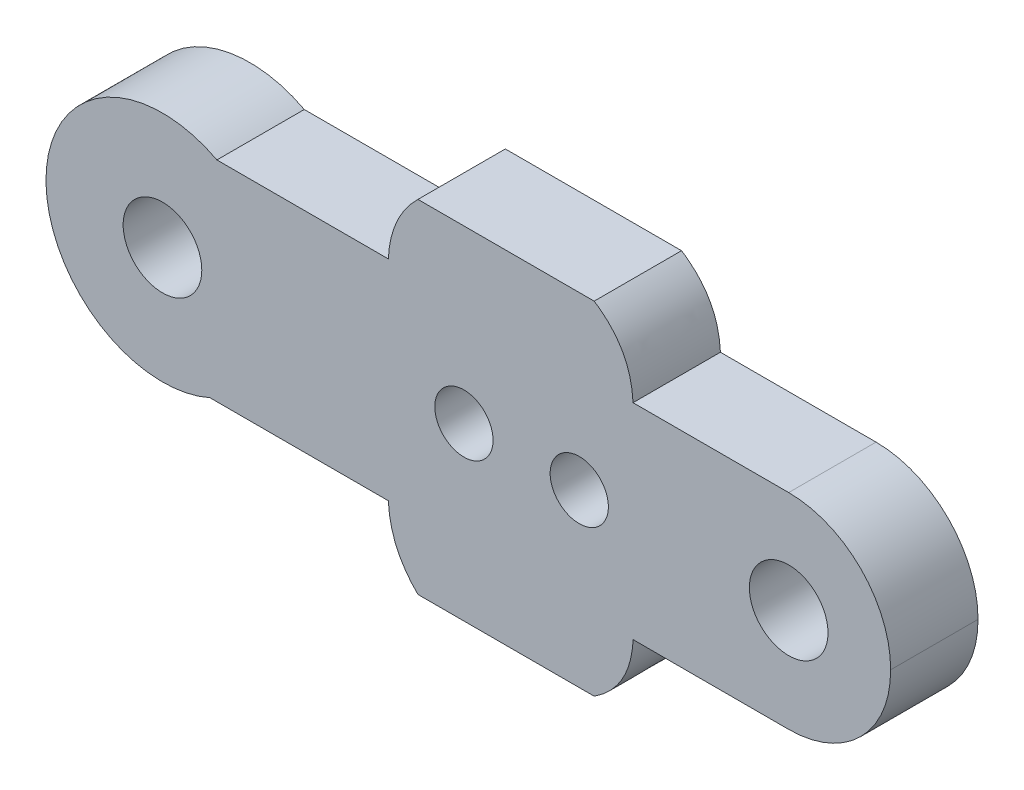
SolidWorks part; units mm, degrees
ref_plane "前视基准面" through (0, 0, 0) normal (0, 0, 1) x (1, 0, 0)
ref_plane "上视基准面" through (0, 0, 0) normal (0, 1, 0) x (1, 0, 0)
ref_plane "右视基准面" through (0, 0, 0) normal (1, 0, 0) x (0, 0, -1)
sketch "草图3" plane through (0, 0, 0) normal (0, 0, 1) x (1, 0, 0)
  line L0 (21.5, 3.5214) -> (16.1563, 3.5214)
  line L1 (1.8683, 3.5953) -> (7.7548, 3.5953)
  line L2 (8.7713, 5.8739) -> (14.8219, 5.8739)
  line L4 (8.7713, -5.8739) -> (14.8219, -5.8739)
  line L5 (1.628, -3.5953) -> (7.7548, -3.5953)
  line L6 (21.5, -3.5214) -> (16.1563, -3.5214)
  circle A0 centre (0, 0.0584) radius 1.35
  circle A1 centre (10.35, 0) radius 1
  circle A2 centre (14.31, 0) radius 1
  circle A3 centre (21.5, 0.0214) radius 1.35
  arc A4 (1.8683, 3.5953) -> (1.628, -3.5953) centre (0, 0.0584) ccw
  arc A5 (24.9999, 0) -> (21.5, 3.5214) centre (21.5, 0.0214) ccw
  arc A6 (24.9999, 0) -> (21.5, -3.5214) centre (21.5, -0.0214) cw
  spline S0 degree 2 poles (7.7548, 3.5953) (7.8164, 4.9447) (8.7713, 5.8739) knots 0 0 0 1 1 1
  spline S1 degree 2 poles (16.1563, 3.5214) (16.0882, 5.0515) (14.8219, 5.8739) knots 0 0 0 1 1 1
  spline S2 degree 2 poles (16.1563, -3.5214) (16.0882, -5.0515) (14.8219, -5.8739) knots 0 0 0 1 1 1
  spline S3 degree 2 poles (7.7548, -3.5953) (7.8164, -4.9447) (8.7713, -5.8739) knots 0 0 0 1 1 1
  dimension "D4" = 2.7
  dimension "D5" = 2
  dimension "D6" = 8
  dimension "D7" = 7
  dimension "D1" = 21.5
  dimension "D2" = 7.19
  dimension "D3" = 3.96
extrude "凸台-拉伸2" add sketch "草图3" along normal blind 3
